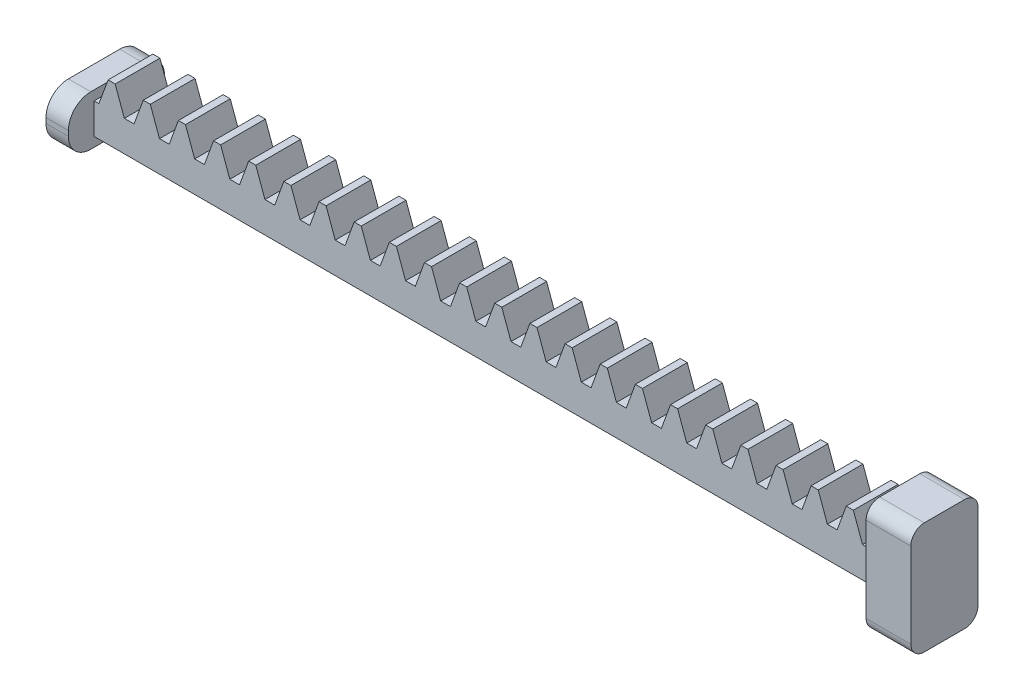
SolidWorks part; units mm, degrees
extrude "Blank" add sketch "BlankSke" against normal blind 10
sketch "BlankSke" plane through (0, 0, 0) normal (0, 0, 1) x (1, 0, 0)
  line L1 (0, 0) -> (175, 0)
  line L2 (0, 0) -> (0, 12.5)
  line L3 (0, 12.5) -> (175, 12.5)
  line L4 (175, 0) -> (175, 12.5)
  dimension "Length" = 175
  dimension "Blank_height" = 12.5
ref_plane "Plane1" through (0, 0, 0) normal (0, 0, 1) x (1, 0, 0)
ref_plane "Plane2" through (0, 0, 0) normal (0, 1, 0) x (1, 0, 0)
ref_plane "Plane3" through (0, 0, 0) normal (1, 0, 0) x (0, 0, -1)
other "Configuration Table"
sketch "HoldingSke" plane through (0, 0, 0) normal (0, 1, 0) x (1, 0, 0)
  line L0 (0, 0) -> (0.0557, 0.3961)
  line L1 (-15, 0) -> (100, 0) construction
  line L2 (0, 0) -> (-2.1039, 2.3779)
  line L3 (0, 0) -> (-11.863, 4.5341)
  line L4 (0, 0) -> (7.8894, 3.5126)
  line L5 (0, 0) -> (-23.7986, -8.8762)
  line L6 (0, 0) -> (-10.5278, -7.1032)
  line L9 (-71.009, 38.7566) -> (93.4372, 98.6101)
  line L10 (-76.2, 4.8779) -> (-66.2, 4.8779)
  line L11 (0, 0) -> (-10, 0)
  line L12 (-76.2, 101.6) -> (-76.113, 101.6)
  line L13 (24.9733, 27.94) -> (52.9518, 28.4284)
  line L14 (24.9733, 27.94) -> (24.9743, 27.94)
  line L15 (24.9733, 27.94) -> (100.4006, 29.5858)
  circle A0 centre (0, 0) radius 19.05
  circle A1 centre (0, 0) radius 5
  circle A2 centre (0, 0) radius 12.7
  dimension "MPH" = 10
  dimension "Diameter" = 38.1
  dimension "Num_teeth" = 24
  dimension "Pitch" = 0.4
  dimension "Show_teeth" = 998
  dimension "Thickness" = 12.7
  dimension "Ap" = 20
  dimension "Pitch_height" = 10
  dimension "Width" = 10
  dimension "Backlash" = 0.087
  dimension "Addendum_fac" = 1
  dimension "Dedendum_fac" = 1.25
  dimension "Clearance_fac" = 0.25
  dimension "Dedendum_add" = 0.001
  dimension "Length" = 175
  dimension "Module" = 2.5
sketch "TooCutSkeIll" plane through (0, 0, 0) normal (0, 0, 1) x (1, 0, 0)
  line L0 (-3.1105, 12.4342) -> (-1.237, 7.2869)
  line L1 (-0.6488, 6.875) -> (0.6488, 6.875)
  line L2 (1.237, 7.2869) -> (3.1105, 12.4342)
  line L3 (175, 12.5) -> (0, 12.5) construction
  line L4 (0, 0) -> (0, 64.897) construction
  line L5 (-13.208, 10) -> (12.954, 10) construction
  line L6 (0, 0) -> (175, 0) construction
  line L7 (2.2245, 10) -> (2.2245, 48.7463) construction
  line L8 (-2.2245, 10) -> (-2.2245, 48.7463) construction
  line L9 (3.2044, 12.5) -> (3.2044, 12.5254)
  line L10 (-3.2044, 12.5) -> (-3.2044, 12.5254)
  line L11 (-3.2044, 12.5254) -> (3.2044, 12.5254)
  arc A0 (0.6488, 6.875) -> (1.237, 7.2869) centre (0.6488, 7.501) ccw
  arc A1 (-1.237, 7.2869) -> (-0.6488, 6.875) centre (-0.6488, 7.501) ccw
  arc A2 (3.2044, 12.5) -> (3.1105, 12.4342) centre (3.2044, 12.4) ccw
  arc A3 (-3.1105, 12.4342) -> (-3.2044, 12.5) centre (-3.2044, 12.4) ccw
  dimension "Pitch_height" = 10
  dimension "Addendum_plus" = 2.5254
  dimension "Pressure_angle" = 20
  dimension "Gap_width" = 4.449
  dimension "Dedendum" = 3.125
extrude "ToothCutIll" [suppressed] cut sketch "TooCutSkeIll" against normal through all
sketch "TooCutSkeSim" plane through (0, 0, 0) normal (0, 0, 1) x (1, 0, 0)
  line L0 (1.0871, 6.875) -> (-1.0871, 6.875)
  line L1 (3.1437, 12.5254) -> (1.0871, 6.875)
  line L2 (0, 17.4625) -> (0, 53.467) construction
  line L3 (3.1437, 12.5254) -> (-3.1437, 12.5254)
  line L6 (-3.1437, 12.5254) -> (-1.0871, 6.875)
  line L9 (-2.2245, 10) -> (2.2245, 10) construction
  line L10 (0, 0) -> (175, 0) construction
  line L11 (2.2245, 10) -> (2.2245, 53.467) construction
  line L12 (-2.2245, 10) -> (-2.2245, 53.467) construction
  dimension "Pitch_height" = 10
  dimension "Addendum_plus" = 2.5254
  dimension "Pressure_angle" = 20
  dimension "Gap_width" = 4.449
  dimension "Dedendum" = 3.125
extrude "ToothCutSim" cut sketch "TooCutSkeSim" against normal through all
pattern_linear "TeethCuts" count 23 spacing 7.854 along (1, 0, 0) of "ToothCutIll", "ToothCutSim"
sketch "Esquisse1" plane through (0, 0, 0) normal (-1, 0, 0) x (0, 0, 1)
  line L0 (-10, 6.875) -> (0, 0) construction
  line L1 (-10, 0) -> (0, 6.875) construction
  line L3 (-10.7364, 9.0033) -> (0.7364, 9.0033)
  line L4 (0, 6.875) -> (-10, 6.875)
  line L5 (-10, 6.875) -> (-10, 0)
  line L6 (-10, 0) -> (0, 0)
  line L7 (0, 0) -> (0, 6.875)
  line L8 (0, 6.875) -> (-10, 6.875)
  line L9 (-10, 6.875) -> (-10, 0)
  line L10 (-10, 0) -> (0, 0)
  line L11 (0, 0) -> (0, 6.875)
  line L12 (-15.7364, 4.0033) -> (-15.7364, 2.8717)
  line L13 (-10.7364, -2.1283) -> (0.7364, -2.1283)
  line L14 (5.7364, 4.0033) -> (5.7364, 2.8717)
  line L15 (-15.7364, 9.0033) -> (5.7364, -2.1283) construction
  line L16 (-15.7364, -2.1283) -> (5.7364, 9.0033) construction
  arc A0 (0.7364, 9.0033) -> (5.7364, 4.0033) centre (0.7364, 4.0033) cw
  arc A1 (0.7364, -2.1283) -> (5.7364, 2.8717) centre (0.7364, 2.8717) ccw
  arc A2 (-15.7364, 2.8717) -> (-10.7364, -2.1283) centre (-10.7364, 2.8717) ccw
  arc A3 (-10.7364, 9.0033) -> (-15.7364, 4.0033) centre (-10.7364, 4.0033) ccw
  point P2 (-5, 3.4375)
  line M9 (0, 6.875) -> (-10, 6.875)
  line M10 (-10, 6.875) -> (-10, 0)
  line M11 (-10, 0) -> (0, 0)
  line M12 (0, 0) -> (0, 6.875)
  dimension "D2" = 5
  dimension "D1" = 0
extrude "Boss.-Extru.1" add sketch "Esquisse1" along normal blind 5 contours L14 L3 L12 L13 M9 M12 M11 M10 | M12 M9 M10 M11
sketch "Esquisse2" plane through (175, 0, 0) normal (1, 0, 0) x (0, 0, -1)
  line L0 (0, 0) -> (10, 9.9668) construction
  line L1 (0, 9.9668) -> (10, 9.9668) construction
  line L2 (10, 0) -> (10, 9.9668) construction
  line L3 (0, 9.9668) -> (10, 0) construction
  line L5 (9.5, 17.4834) -> (0.5, 17.4834)
  line L6 (12.5, 14.4834) -> (12.5, -4.5166)
  line L7 (9.5, -7.5166) -> (0.5, -7.5166)
  line L8 (-2.5, 14.4834) -> (-2.5, -4.5166)
  line L9 (12.5, 17.4834) -> (-2.5, -7.5166) construction
  line L10 (12.5, -7.5166) -> (-2.5, 17.4834) construction
  arc A0 (0.5, 17.4834) -> (-2.5, 14.4834) centre (0.5, 14.4834) ccw
  arc A1 (9.5, 17.4834) -> (12.5, 14.4834) centre (9.5, 14.4834) cw
  arc A2 (12.5, -4.5166) -> (9.5, -7.5166) centre (9.5, -4.5166) cw
  arc A3 (0.5, -7.5166) -> (-2.5, -4.5166) centre (0.5, -4.5166) cw
  point P11 (5, 4.9834)
  dimension "D3" = 3
  dimension "D1" = 25
  dimension "D2" = 15
extrude "Boss.-Extru.2" add sketch "Esquisse2" along normal blind 10
equation "' \"Module@HoldingSke\" = 6.35"
equation "' \"Num_teeth@HoldingSke\" = 12"
equation "' \"Ap@HoldingSke\" =  20"
equation "' \"Ap@HoldingSke\" = 20"
equation "' \"Width@HoldingSke\" = 0.25 * 25.4"
equation "' \"Show_teeth@HoldingSke\" = 500"
equation "' \"Backlash@HoldingSke\" = 0.009 * 25.4"
equation "' \"Addendum_fac@HoldingSke\" = 1.0"
equation "' \"Dedendum_fac@HoldingSke\" = 1.25"
equation "' \"Dedendum_add@HoldingSke\" = 0.00005 * 25.4"
equation "' \"Clearance_fac@HoldingSke\" = 0.25"
equation "' \"Pitch_height@HoldingSke\" = 1 * 25.4"
equation "' \"Length@HoldingSke\" = 4.71 * 25.4"
equation "\"Pitch@HoldingSke\" = 1 / \"Module@HoldingSke\""
equation "\"MPH@HoldingSke\" = \"Dedendum_fac@HoldingSke\" / \"Pitch@HoldingSke\" + 2 * \"Dedendum_add@HoldingSke\" + 0.002 * 25.4"
equation "\"MPH@HoldingSke\" = ((sgn( \"MPH@HoldingSke\" - \"Pitch_height@HoldingSke\")+1)*( \"MPH@HoldingSke\" - \"Pitch_height@HoldingSke\"))/2 + \"Pitch_height@HoldingSke\""
equation "\"Blank_height@BlankSke\" = \"Pitch_height@HoldingSke\" + \"Addendum_fac@HoldingSke\"  / \"Pitch@HoldingSke\" "
equation "\"Length@BlankSke\" =  \"Length@HoldingSke\""
equation "\"Face_width@Blank\" = \"Width@HoldingSke\""
equation "\"Pressure_angle@TooCutSkeIll\" = \"Ap@HoldingSke\""
equation "\"Addendum_plus@TooCutSkeIll\" =  \"Addendum_fac@HoldingSke\"  / \"Pitch@HoldingSke\" + 0.001 *25.4"
equation "\"Dedendum@TooCutSkeIll\" = \"Dedendum_fac@HoldingSke\"  / \"Pitch@HoldingSke\""
equation "\"Pitch_height@TooCutSkeIll\" =  \"MPH@HoldingSke\""
equation "\"Gap_width@TooCutSkeIll\" = 3.14159265 / 2 / \"Pitch@HoldingSke\" + 6 * \"Backlash@HoldingSke\""
equation "\"Pressure_angle@TooCutSkeSim\" = \"Ap@HoldingSke\""
equation "\"Addendum_plus@TooCutSkeSim\" =  \"Addendum_fac@HoldingSke\"  / \"Pitch@HoldingSke\" + 0.001 * 25.4"
equation "\"Dedendum@TooCutSkeSim\" = \"Dedendum_fac@HoldingSke\"  / \"Pitch@HoldingSke\""
equation "\"Pitch_height@TooCutSkeSim\" =  \"MPH@HoldingSke\""
equation "\"Gap_width@TooCutSkeSim\" = 3.14159265 / 2 / \"Pitch@HoldingSke\" + 6 * \"Backlash@HoldingSke\""
equation "\"Root_fillet@TooCutSkeIll\" = \"Clearance_fac@HoldingSke\" / \"Pitch@HoldingSke\" + \"Dedendum_add@HoldingSke\""
equation "\"Break_rad@TooCutSkeIll\" = 0.02 / \"Pitch@HoldingSke\" * 2"
equation "\"Linear_pitch@TeethCuts\" = 3.14159265 / \"Pitch@HoldingSke\""
equation "\"Num_teeth@HoldingSke\" = int( ( \"Length@HoldingSke\" + 0 ) / (3.14159265 / \"Pitch@HoldingSke\")) + 0.9999  + 1"
equation " \"Num_teeth@TeethCuts\" = int( \"Show_teeth@HoldingSke\" ) + 1"
equation " \"Num_teeth@TeethCuts\" = ((sgn( \"Num_teeth@TeethCuts\" - \"Num_teeth@HoldingSke\" )-1)*( \"Num_teeth@TeethCuts\" - \"Num_teeth@HoldingSke\" ))/-2+ \"Num_teeth@HoldingSke\""
equation " \"Num_teeth@TeethCuts\" = ((sgn( \"Num_teeth@TeethCuts\" - 2.0)+1)*( \"Num_teeth@TeethCuts\" - 2.0))/2 +2.0"
